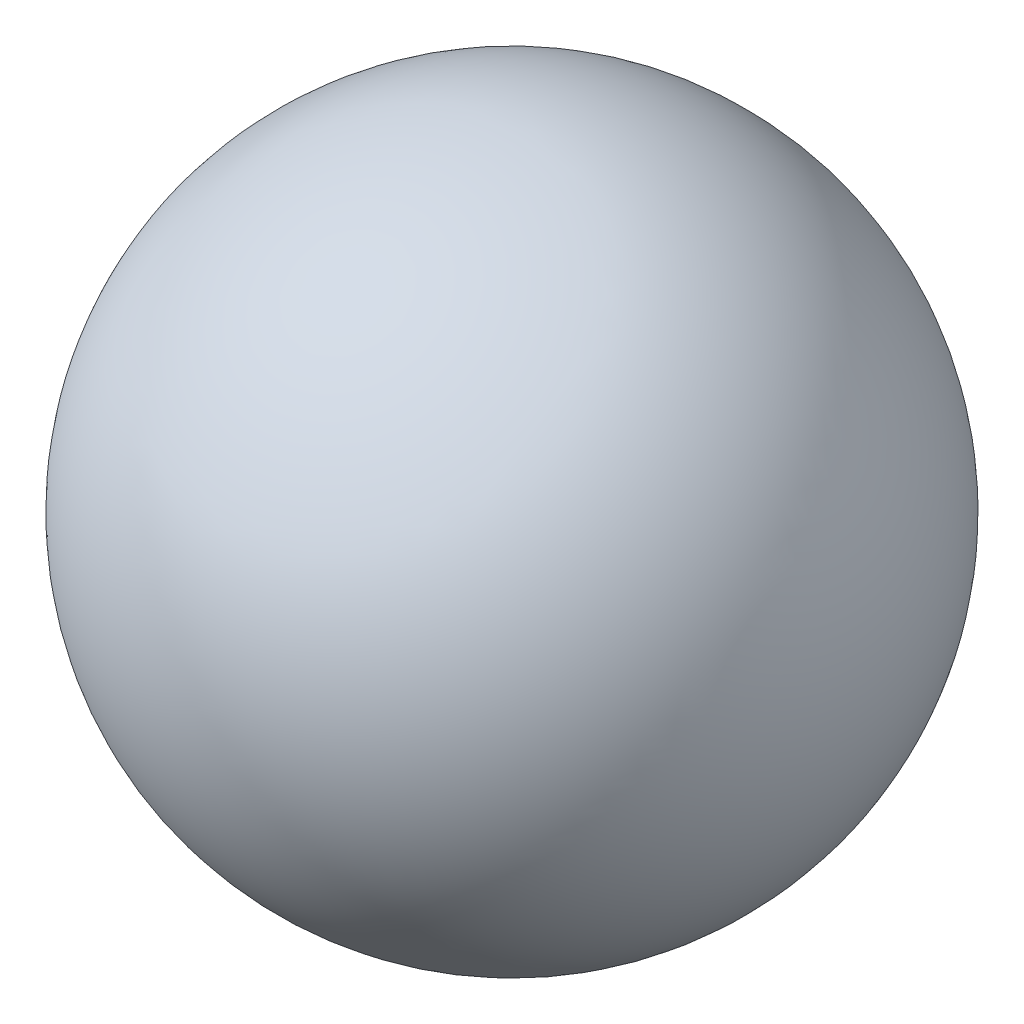
SolidWorks part; units mm, degrees
ref_plane "Front Plane" through (0, 0, 0) normal (0, 0, 1) x (1, 0, 0)
ref_plane "Top Plane" through (0, 0, 0) normal (0, 1, 0) x (1, 0, 0)
ref_plane "Right Plane" through (0, 0, 0) normal (1, 0, 0) x (0, 0, -1)
sketch "Sketch1" plane through (0, 0, 0) normal (0, 0, 1) x (1, 0, 0)
  line L0 (-12, 0) -> (12, 0)
  arc A0 (-12, 0) -> (12, 0) centre (0, 0) ccw
  dimension "D2" = 12
  dimension "D1" = 24
revolve "Revolve-Thin1" add sketch "Sketch1" angle 360 about L0
